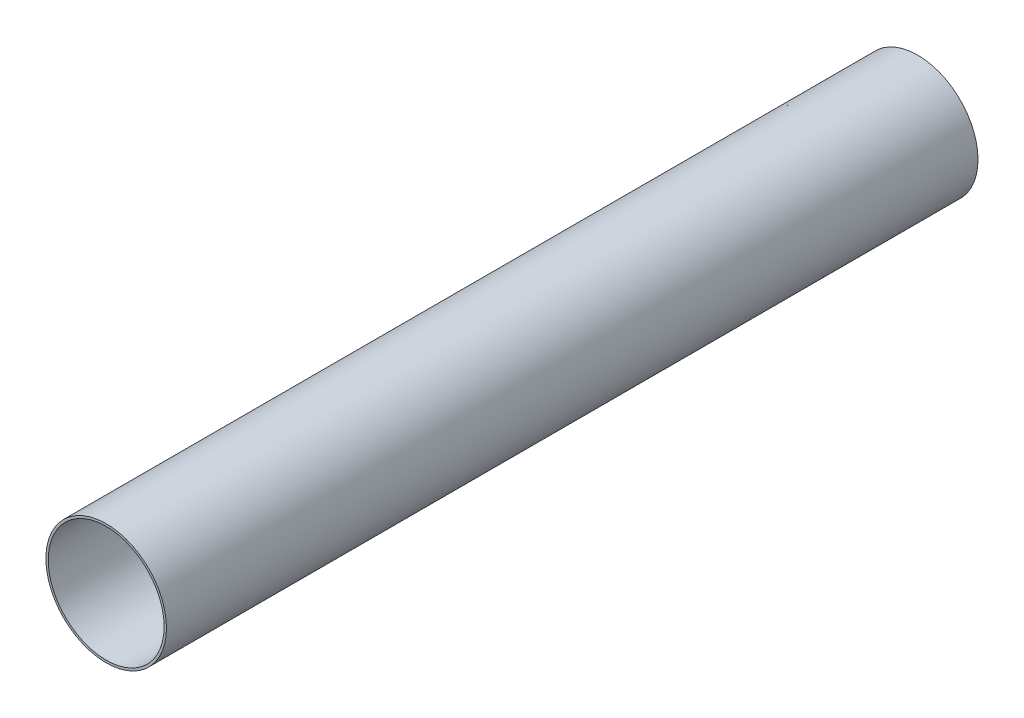
SolidWorks part; units mm, degrees
ref_plane "Front Plane" through (0, 0, 0) normal (0, 0, 1) x (1, 0, 0)
ref_plane "Top Plane" through (0, 0, 0) normal (0, 1, 0) x (1, 0, 0)
ref_plane "Right Plane" through (0, 0, 0) normal (1, 0, 0) x (0, 0, -1)
sketch "Sketch1" plane through (0, 0, 0) normal (0, 0, 1) x (1, 0, 0)
  circle A0 centre (0, 0) radius 75
  circle A1 centre (0, 0) radius 78
  dimension "D1" = 3
extrude "Boss-Extrude1" add sketch "Sketch1" against normal up to surface (1050 mm away)
